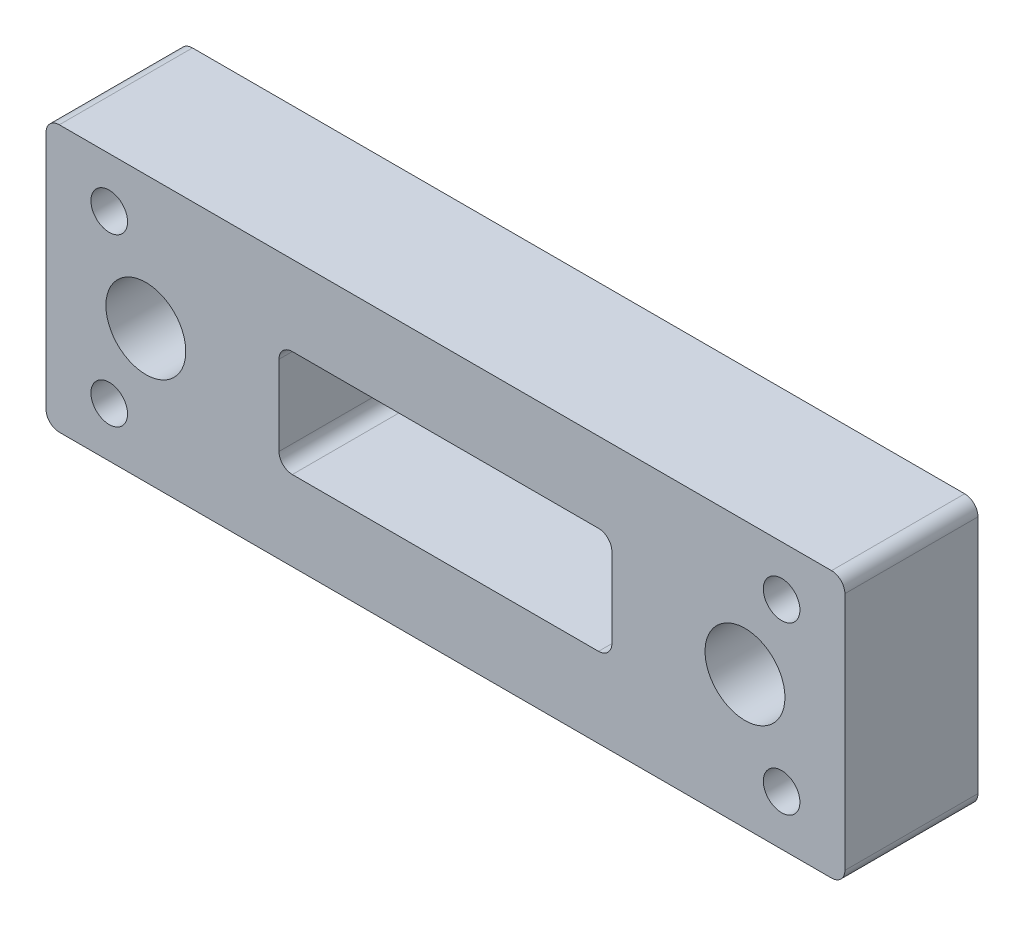
SolidWorks part; units mm, degrees
ref_plane "前视基准面" through (0, 0, 0) normal (0, 0, 1) x (1, 0, 0)
ref_plane "上视基准面" through (0, 0, 0) normal (0, 1, 0) x (1, 0, 0)
ref_plane "右视基准面" through (0, 0, 0) normal (1, 0, 0) x (0, 0, -1)
sketch "草图1" plane through (0, 0, 0) normal (0, 0, 1) x (1, 0, 0)
  line L1 (-60, 20) -> (60, 20)
  line L2 (-60, 20) -> (-60, -20)
  line L3 (-60, -20) -> (60, -20)
  line L4 (60, 20) -> (60, -20)
  dimension "D1" = 120
  dimension "D2" = 40
  dimension "D3" = 20
  dimension "D4" = 60
extrude "凸台-拉伸1" add sketch "草图1" along normal blind 20
sketch "草图2" plane through (0, 0, 20) normal (0, 0, 1) x (1, 0, 0)
  line L0 (0, 0) -> (0, 50000) construction
  line L2 (0, 0) -> (-50000, 0) construction
  circle A0 centre (45, 0) radius 6
  circle A1 centre (50.5, 12.5) radius 2.75
  circle A2 centre (50.5, -12.5) radius 2.75
  circle A3 centre (-50.5, -12.5) radius 2.75
  circle A4 centre (-50.5, 12.5) radius 2.75
  circle A5 centre (-45, 0) radius 6
  dimension "D1" = 45
  dimension "D4" = 5.5
  dimension "D5" = 12
  dimension "D6" = 12.5
  dimension "D2" = 50.5
  dimension "D3" = 12.5
extrude "切除-拉伸1" cut sketch "草图2" against normal blind 20
fillet "圆角1" radius 2 4 edges at (-60, 20, 10) (-60, -20, 10) (60, 20, 10) (60, -20, 10)
sketch "草图3" plane through (0, 0, 20) normal (0, 0, 1) x (1, 0, 0)
  line L0 (58, 20) -> (-58, 20) construction
  line L1 (-25, 8) -> (25, 8)
  line L2 (-25, 8) -> (-25, -8)
  line L3 (-25, -8) -> (25, -8)
  line L4 (25, 8) -> (25, -8)
  line L5 (-58, -20) -> (58, -20) construction
  line L6 (60, -18) -> (60, 18) construction
  line L7 (-60, 18) -> (-60, -18) construction
  dimension "D1" = 12
  dimension "D2" = 12
  dimension "D3" = 35
  dimension "D4" = 35
extrude "切除-拉伸2" cut sketch "草图3" against normal through all
fillet "圆角2" radius 2 4 edges at (25, -8, 10) (-25, -8, 10) (-25, 8, 10) (25, 8, 10)
